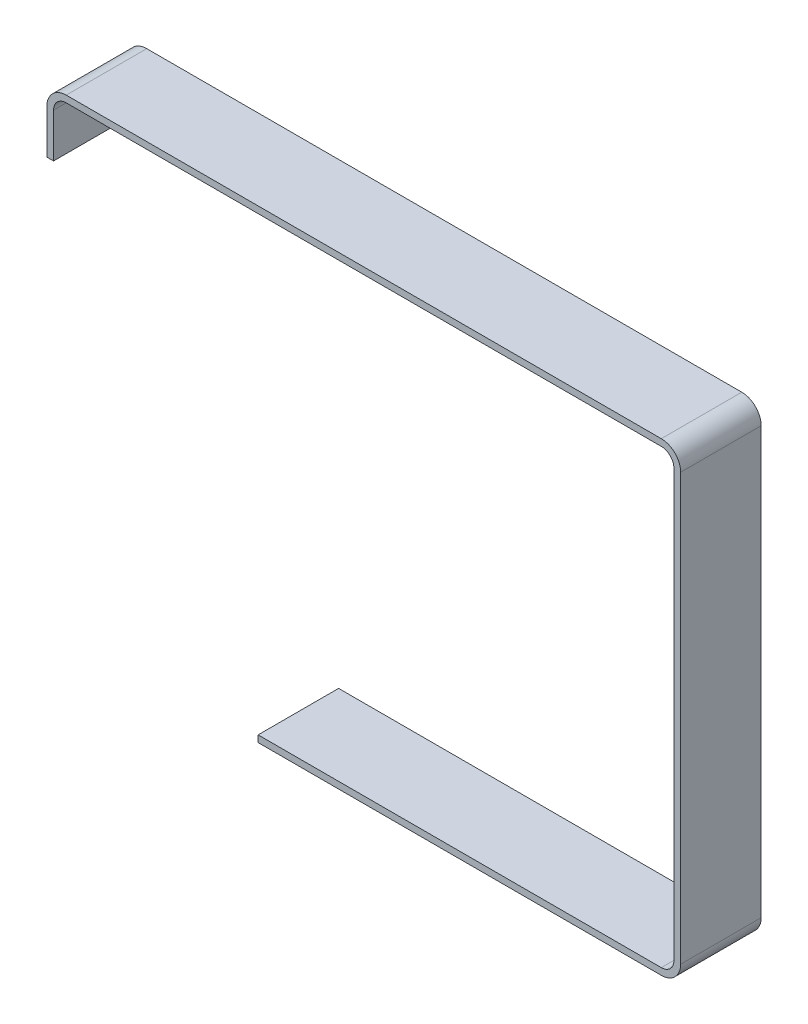
SolidWorks part; units mm, degrees
ref_plane "Front Plane" through (0, 0, 0) normal (0, 0, 1) x (1, 0, 0)
ref_plane "Top Plane" through (0, 0, 0) normal (0, 1, 0) x (1, 0, 0)
ref_plane "Right Plane" through (0, 0, 0) normal (1, 0, 0) x (0, 0, -1)
sketch "Sketch1" plane through (0, 0, 0) normal (0, 0, 1) x (1, 0, 0)
  line L0 (-100, 0) -> (0, 0)
  line L1 (0, 0) -> (0, 110)
  line L2 (0, 110) -> (-150, 110)
  line L3 (-150, 110) -> (-150, 95)
  line L4 (-100, 1.5875) -> (-1.5875, 1.5875)
  line L5 (-1.5875, 1.5875) -> (-1.5875, 108.4125)
  line L6 (-1.5875, 108.4125) -> (-148.4125, 108.4125)
  line L7 (-148.4125, 108.4125) -> (-148.4125, 95)
  line L8 (-150, 95) -> (-148.4125, 95)
  line L9 (-100, 0) -> (-100, 1.5875)
  dimension "D1" = 100
  dimension "D2" = 110
  dimension "D3" = 150
  dimension "D4" = 15
  dimension "D5" = 1.5875
extrude "Boss-Extrude1" add sketch "Sketch1" along normal blind 19.05
fillet "Fillet1" radius 3 3 edges at (-1.5875, 1.5875, 9.525) (-1.5875, 108.4125, 9.525) (-148.4125, 108.4125, 9.525)
fillet "Fillet2" radius 4.5875 3 edges at (0, 0, 9.525) (0, 110, 9.525) (-150, 110, 9.525)
